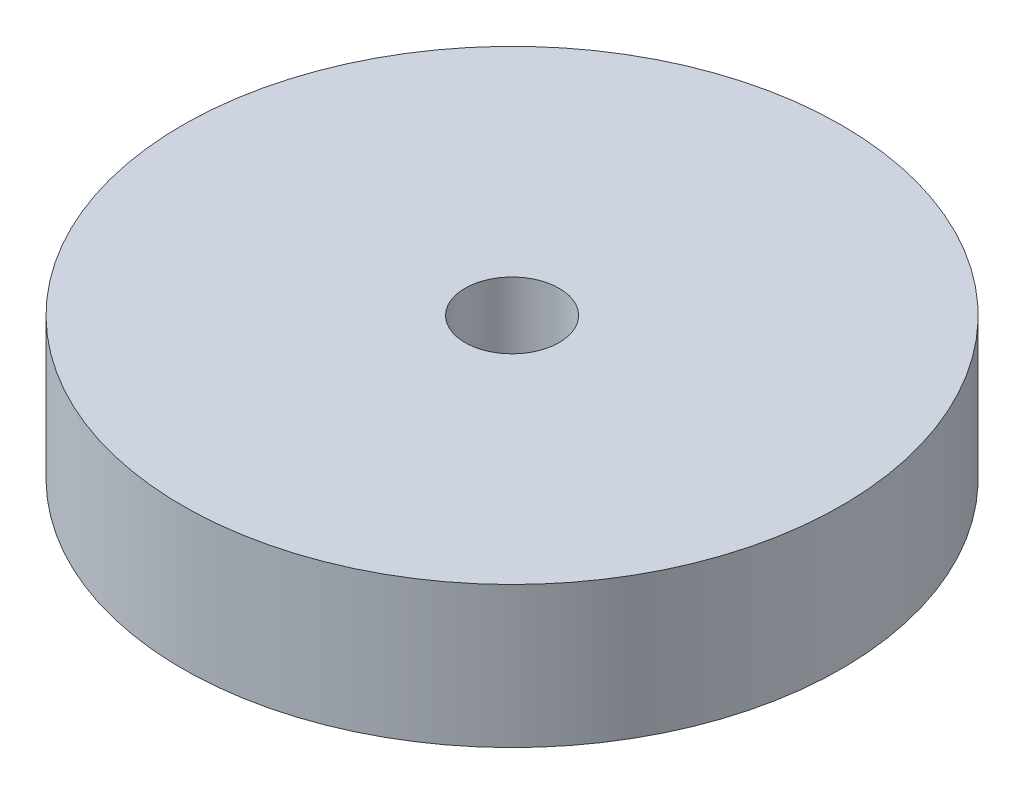
SolidWorks part; units mm, degrees
material "Plain Carbon Steel"
ref_plane "Front Plane" through (0, 0, 0) normal (0, 0, 1) x (1, 0, 0)
ref_plane "Top Plane" through (0, 0, 0) normal (0, 1, 0) x (1, 0, 0)
ref_plane "Right Plane" through (0, 0, 0) normal (1, 0, 0) x (0, 0, -1)
other "Center of Mass"
sketch "Sketch1" plane through (0, 0, 0) normal (0, 0, 1) x (1, 0, 0)
  line L0 (-9.1173, 16.4724) -> (-9.1173, 14.3217) construction
  line L5 (-9.1173, 12.7) -> (-9.1173, 32.9797) construction
  line L8 (-14.1173, 7.5191) -> (-11.6173, 7.5191)
  line L9 (-26.6173, 12.5191) -> (-26.6173, 5.0191)
  line L10 (-26.6173, 5.0191) -> (-21.6173, 5.0191)
  line L11 (-21.6173, 10.0191) -> (-21.6173, 5.0191)
  line L12 (-11.6173, 7.5191) -> (-11.6173, 12.5191)
  line L13 (-26.6173, 12.5191) -> (-11.6173, 12.5191)
  line L14 (-21.6173, 10.0191) -> (-14.1173, 10.0191)
  line L15 (-14.1173, 10.0191) -> (-14.1173, 7.5191)
  dimension "D1" = 2.5
  dimension "D2" = 12.5
  dimension "D3" = 17.5
  dimension "D4" = 5
  dimension "D5" = 5
  dimension "D6" = 7.5
  dimension "D7" = 2.5
revolve "Revolve1" add sketch "Sketch1" angle 360 about L5
